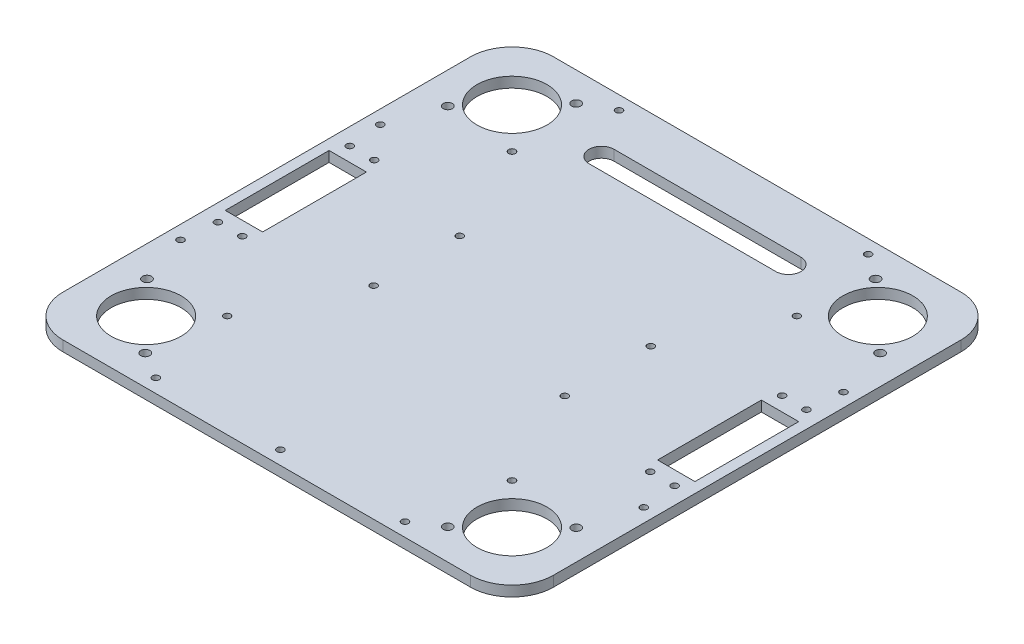
SolidWorks part; units mm, degrees
ref_plane "Front Plane" through (0, 0, 0) normal (0, 0, 1) x (1, 0, 0)
ref_plane "Top Plane" through (0, 0, 0) normal (0, 1, 0) x (1, 0, 0)
ref_plane "Right Plane" through (0, 0, 0) normal (1, 0, 0) x (0, 0, -1)
sketch "Sketch1" plane through (0, 0, 0) normal (0, 1, 0) x (1, 0, 0)
  line L1 (-150, 150) -> (150, 150)
  line L2 (-150, 150) -> (-150, -150)
  line L3 (-150, -150) -> (150, -150)
  line L4 (150, 150) -> (150, -150)
  line L5 (-150, 150) -> (150, -150) construction
  line L6 (-150, -150) -> (150, 150) construction
  point P0 (0, 0)
  dimension "D1" = 300
  dimension "30cm" = 300
extrude "Boss-Extrude1" add sketch "Sketch1" along normal blind 6.35
sketch "Sketch2" plane through (0, 6.35, 0) normal (0, 1, 0) x (1, 0, 0)
  line L0 (111.9, -101.2886) -> (111.9, 49898.7114) construction
  line L1 (-111.9, 7.7624) -> (-111.9, 50007.7624) construction
  line L2 (-244.363, -111.9) -> (49755.637, -111.9) construction
  line L3 (-269.6272, 111.9) -> (49730.3728, 111.9) construction
  line L4 (-150, 150) -> (-150, -150) construction
  line L5 (-150, -150) -> (150, -150) construction
  line L6 (150, -150) -> (150, 150) construction
  line L7 (150, 150) -> (-150, 150) construction
  line L8 (0, 150) -> (0, 50150) construction
  line L9 (-150, 0) -> (-50150, 0) construction
  line L23 (-150, 150) -> (150, -150) construction
  line L24 (-57.15, 111.9) -> (57.15, 111.9) construction
  line L25 (-57.15, 119.55) -> (57.15, 119.55)
  line L26 (-57.15, 104.25) -> (57.15, 104.25)
  line L27 (-111.9, 111.9) -> (33974.81, 36691.8972) construction
  line L28 (111.9, 111.9) -> (-36468.0972, 34198.61) construction
  line L29 (111.9, -111.9) -> (35936.5707, 34767.7928) construction
  line L30 (-111.9, -111.9) -> (-34991.5928, 35712.7707) construction
  circle A0 centre (-87.1382, 87.1382) radius 2.0828
  circle A1 centre (87.1382, 87.1382) radius 2.0828
  circle A2 centre (87.1382, -87.1382) radius 2.0828
  circle A3 centre (-87.1382, -87.1382) radius 2.0828
  circle A5 centre (-141.6688, 61.1) radius 2.0828
  circle A7 centre (-141.6688, -61.1) radius 2.0828
  circle A8 centre (-76.2, -141.6688) radius 2.0828
  circle A9 centre (76.2, -141.6688) radius 2.0828
  circle A10 centre (0, -141.6688) radius 2.0828
  circle A11 centre (-76.2, 141.6688) radius 2.0828
  circle A13 centre (76.2, 141.6688) radius 2.0828
  circle A15 centre (141.6688, 61.1) radius 2.0828
  circle A17 centre (141.6688, -61.1) radius 2.0828
  circle A18 centre (-139.6622, 40.4492) radius 2.0828
  circle A19 centre (-124.7778, 40.4492) radius 2.0828
  circle A20 centre (-139.6622, -40.2212) radius 2.0828
  circle A21 centre (-124.7778, -40.2212) radius 2.0828
  circle A22 centre (124.7778, 40.4492) radius 2.0828
  circle A23 centre (139.6622, 40.4492) radius 2.0828
  circle A24 centre (124.7778, -40.2212) radius 2.0828
  circle A25 centre (139.6622, -40.2212) radius 2.0828
  arc A26 (-57.15, 119.55) -> (-57.15, 104.25) centre (-57.15, 111.9) ccw
  arc A27 (57.15, 104.25) -> (57.15, 119.55) centre (57.15, 111.9) ccw
  circle A28 centre (-58.4383, 26.4393) radius 2.0828
  circle A29 centre (-58.4383, -26.2113) radius 2.0828
  circle A30 centre (58.4383, 26.4393) radius 2.0828
  circle A31 centre (58.4383, -26.2113) radius 2.0828
  point P17 (0, 150)
  point P21 (-150, 0)
  point P22 (-57.15, 0)
  point P109 (0, 111.9)
  circle B0 centre (-131.28, -91.9949) radius 2.7781
  circle B1 centre (-111.9, -111.9) radius 21.4312
  line B2 (-111.9, -111.9) -> (35712.7707, 34767.7928) construction
  circle B3 centre (-92.52, -131.8051) radius 2.7781
  line B4 (120.79, 0) -> (-120.79, 0) construction
  line B5 (143.65, -31.75) -> (120.79, -31.75)
  line B6 (143.65, -31.75) -> (143.65, 31.75)
  line B7 (143.65, 31.75) -> (120.79, 31.75)
  line B8 (120.79, -31.75) -> (120.79, 31.75)
  line B9 (-120.79, -31.75) -> (-143.65, -31.75)
  line B10 (-120.79, -31.75) -> (-120.79, 31.75)
  line B11 (-120.79, 31.75) -> (-143.65, 31.75)
  line B12 (-143.65, -31.75) -> (-143.65, 31.75)
  line B13 (0, -51.8106) -> (0, -50051.8106) construction
  circle B14 centre (91.9949, -131.28) radius 2.7781
  circle B15 centre (111.9, -111.9) radius 21.4312
  circle B16 centre (131.8051, -92.52) radius 2.7781
  circle B17 centre (91.5752, 130.8394) radius 2.7781
  circle B18 centre (111.9, 111.9) radius 21.4312
  circle B19 centre (132.2248, 92.9606) radius 2.7781
  circle B20 centre (-130.8394, 91.5752) radius 2.7781
  circle B21 centre (-111.9, 111.9) radius 21.4312
  circle B22 centre (-92.9606, 132.2248) radius 2.7781
  dimension "D8" = 4.1656
  dimension "D1" = 38.1
  dimension "D2" = 38.1
  dimension "D3" = 38.1
  dimension "D4" = 90
  dimension "1.5" = 38.1
  dimension "D9" = 88.9
  dimension "D10" = 15.3
  dimension "D11" = 114.3
  dimension "D12" = 90
sketch_block_instance "Block1-2"
sketch_block "Block1" parameters "D1"=25.4662, "D3"=7.6276, "D2"=64.723
sketch_block_instance "Block2-1"
sketch_block "Block2" parameters "D1"=20.32, "D2"=20.32, "D3"=246.66, "D4"=54.356
sketch_block_instance "Block1-5"
sketch_block_instance "Block1-6"
sketch_block_instance "Block1-7"
extrude "Cut-Extrude1" cut sketch "Sketch2" against normal through all
fillet "Fillet1" radius 25.4 4 edges at (150, 3.175, -150) (-150, 3.175, -150) (-150, 3.175, 150) (150, 3.175, 150)
